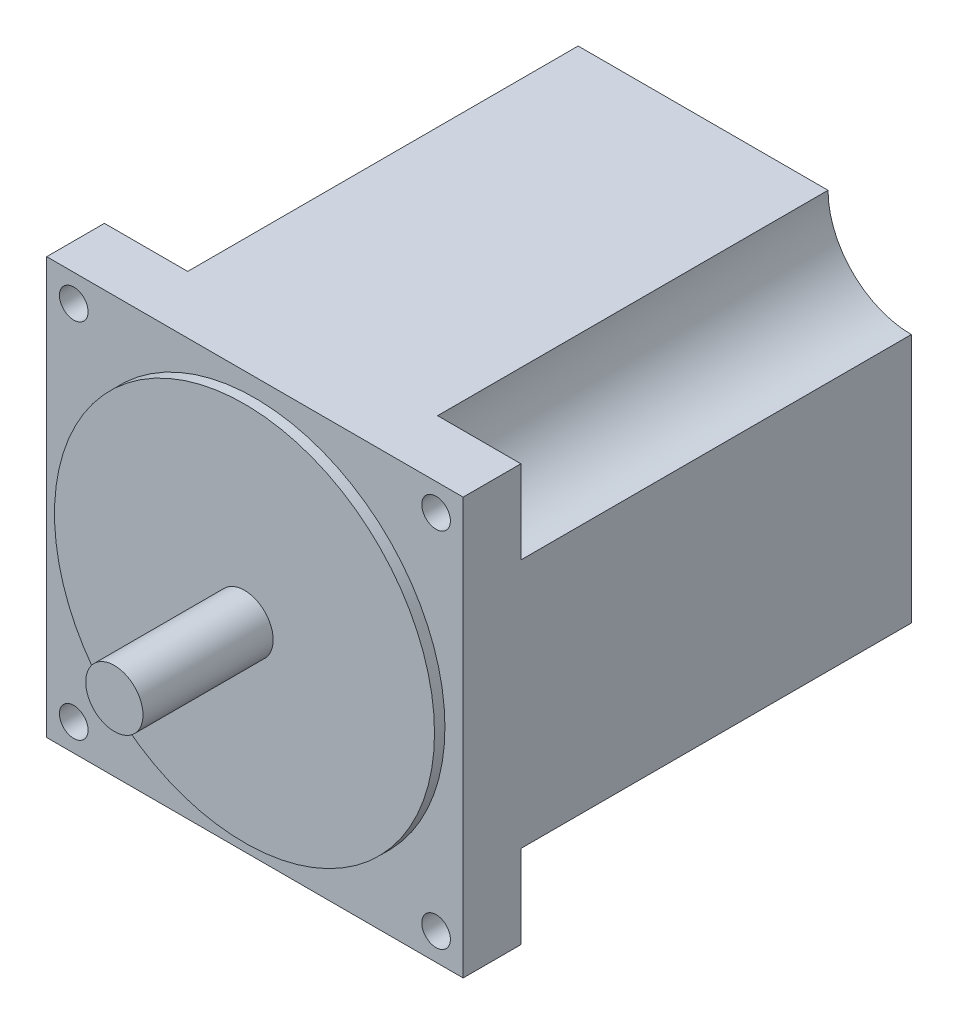
SolidWorks part; units mm, degrees
ref_plane "Front Plane" through (0, 0, 0) normal (0, 0, 1) x (1, 0, 0)
ref_plane "Top Plane" through (0, 0, 0) normal (0, 1, 0) x (1, 0, 0)
ref_plane "Right Plane" through (0, 0, 0) normal (1, 0, 0) x (0, 0, -1)
sketch "Sketch2" plane through (0, 0, 0) normal (0, 0, 1) x (1, 0, 0)
  line L1 (40, -40) -> (-40, -40)
  line L2 (40, -40) -> (40, 40)
  line L3 (40, 40) -> (-40, 40)
  line L4 (-40, -40) -> (-40, 40)
  line L5 (40, -40) -> (-40, 40) construction
  line L6 (40, 40) -> (-40, -40) construction
  point P0 (0, 0)
  dimension "D1" = 80
  dimension "D2" = 80
extrude "Boss-Extrude1" add sketch "Sketch2" along normal blind 86.09 contours L3 L4 L1 L2
sketch "Sketch3" plane through (0, 0, 86.09) normal (0, 0, 1) x (1, 0, 0)
  line L1 (34.8, -34.8) -> (-34.8, -34.8) construction
  line L2 (34.8, -34.8) -> (34.8, 34.8) construction
  line L3 (34.8, 34.8) -> (-34.8, 34.8) construction
  line L4 (-34.8, -34.8) -> (-34.8, 34.8) construction
  line L5 (34.8, -34.8) -> (-34.8, 34.8) construction
  line L6 (34.8, 34.8) -> (-34.8, -34.8) construction
  circle A0 centre (-34.8, 34.8) radius 2.75
  circle A1 centre (34.8, 34.8) radius 2.75
  circle A2 centre (-34.8, -34.8) radius 2.75
  circle A3 centre (34.8, -34.8) radius 2.75
  point P0 (0, 0)
  dimension "D3" = 5.5
  dimension "D4" = 5.5
  dimension "D5" = 5.5
  dimension "D6" = 5.5
  dimension "D1" = 69.6
  dimension "D2" = 69.6
extrude "Cut-Extrude1" cut sketch "Sketch3" against normal through all
sketch "Sketch4" plane through (0, 0, 86.09) normal (0, 0, 1) x (1, 0, 0)
  circle A0 centre (0, 0) radius 36.5
  dimension "D1" = 73
extrude "Boss-Extrude2" add sketch "Sketch4" along normal blind 2
sketch "Sketch5" plane through (0, 0, 88.09) normal (0, 0, 1) x (1, 0, 0)
  circle A0 centre (0, 0) radius 5.5
  dimension "D1" = 11
extrude "Boss-Extrude3" add sketch "Sketch5" along normal blind 25
sketch "Sketch6" plane through (0, 0, 0) normal (0, 0, -1) x (-1, 0, 0)
  line L0 (-40, 40) -> (40, 40) construction
  line L1 (-40, -40) -> (-40, 40) construction
  line L2 (-40, -40) -> (40, -40) construction
  line L3 (40, -40) -> (40, 40) construction
  line L5 (40, -40) -> (-40, -40)
  line L6 (40, -40) -> (40, 40)
  line L7 (40, 40) -> (-40, 40)
  line L8 (-40, -40) -> (-40, 40)
  line L9 (40, -40) -> (-40, 40) construction
  line L10 (40, 40) -> (-40, -40) construction
  arc A0 (-24, 40) -> (-40, 24) centre (-40, 40) cw
  arc A1 (-40, -24) -> (-24, -40) centre (-40, -40) cw
  arc A2 (24, -40) -> (40, -24) centre (40, -40) cw
  arc A3 (24, 40) -> (40, 24) centre (40, 40) ccw
  point P24 (0, 0)
  circle M1 centre (-34.8, 34.8) radius 2.75
  circle M2 centre (34.8, -34.8) radius 2.75
  circle M3 centre (-34.8, -34.8) radius 2.75
  circle M4 centre (34.8, 34.8) radius 2.75
  line M5 (-40, 40) -> (-40, -40)
  line M6 (-40, -40) -> (40, -40)
  line M7 (40, -40) -> (40, 40)
  line M8 (40, 40) -> (-40, 40)
  dimension "D1" = 16
  dimension "D2" = 16
  dimension "D3" = 16
  dimension "D4" = 16
extrude "Cut-Extrude2" cut sketch "Sketch6" against normal blind 75 contours A0 L7 M5 M1 | A3 M8 M7 M4 | A2 M6 M7 M2 | A1 M5 M6 M3
sketch "Sketch7" plane through (0, 0, 0) normal (0, 0, -1) x (-1, 0, 0)
  circle A0 centre (0, 0) radius 4.006
  dimension "D1" = 8.012
extrude "Boss-Extrude4" add sketch "Sketch7" along normal blind 13.5
